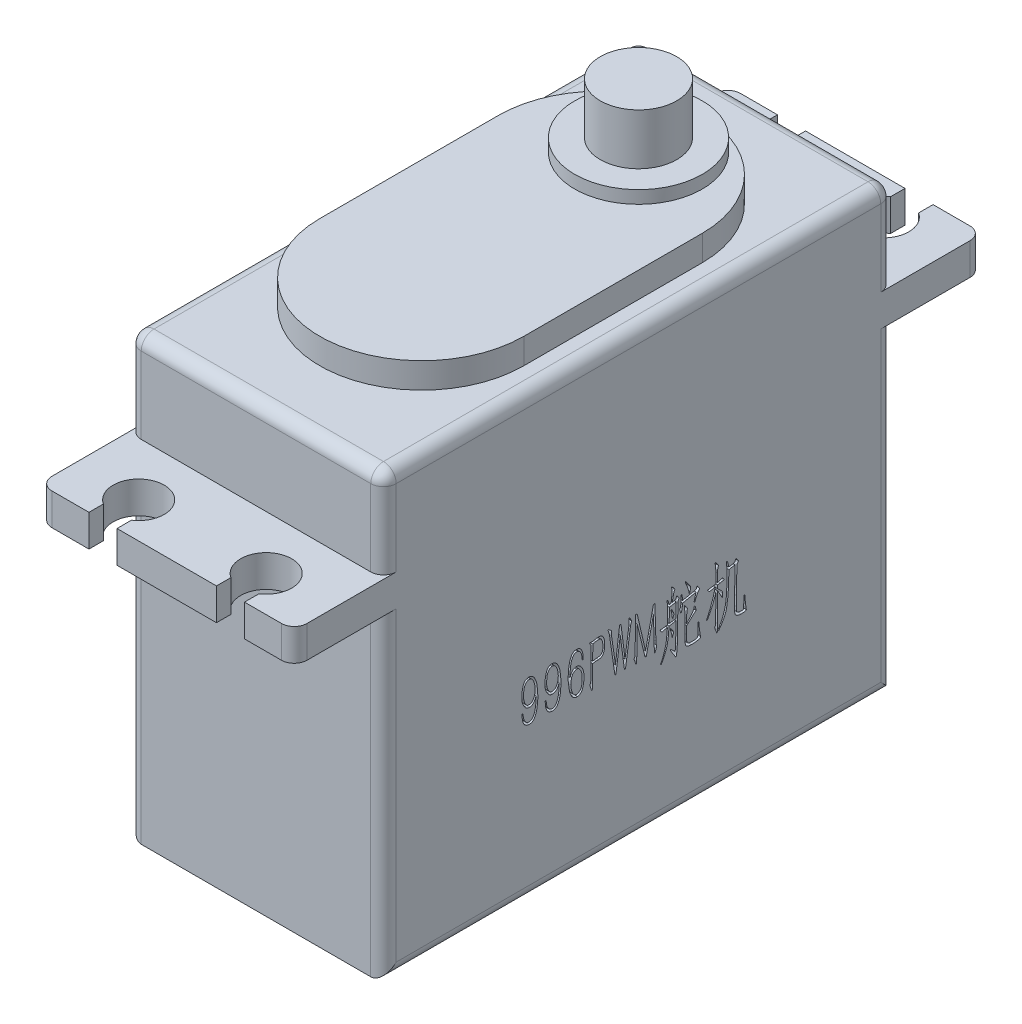
SolidWorks part; units mm, degrees
material "6061 合金"
ref_plane "前视基准面" through (0, 0, 0) normal (0, 0, 1) x (1, 0, 0)
ref_plane "上视基准面" through (0, 0, 0) normal (0, 1, 0) x (1, 0, 0)
ref_plane "右视基准面" through (0, 0, 0) normal (1, 0, 0) x (0, 0, -1)
sketch "草图1" plane through (0, 0, 0) normal (0, 1, 0) x (1, 0, 0)
  line L1 (-10, -20) -> (10, -20)
  line L2 (-10, -20) -> (-10, 20)
  line L3 (-10, 20) -> (10, 20)
  line L4 (10, -20) -> (10, 20)
  line L5 (-10, -20) -> (10, 20) construction
  line L6 (-10, 20) -> (10, -20) construction
  point P0 (0, 0)
  dimension "D1" = 20
  dimension "D2" = 40
extrude "凸台-拉伸1" add sketch "草图1" along normal blind 34.5
sketch "草图2" plane through (0, 34.5, 0) normal (0, 1, 0) x (1, 0, 0)
  line L0 (0, -7) -> (0, 7) construction
  line L1 (-8, -7) -> (-8, 7)
  line L2 (8, -7) -> (8, 7)
  arc A0 (-8, -7) -> (8, -7) centre (0, -7) ccw
  arc A1 (8, 7) -> (-8, 7) centre (0, 7) ccw
  point P2 (0, 0)
  point P8 (0, 15)
  point P9 (0, -15)
  dimension "D1" = 8
  dimension "D2" = 30
extrude "凸台-拉伸2" add sketch "草图2" along normal blind 2
ref_plane "基准面1" through (0, 25, 0) normal (0, -1, 0) x (-1, 0, 0)
sketch "草图3" plane through (0, 25, 0) normal (0, -1, 0) x (-1, 0, 0)
  line L0 (-6.1, 27) -> (-6.1, 25.8703)
  line L1 (-9, -27) -> (-6.1, -27)
  line L2 (-10, -26) -> (-10, 26)
  line L3 (-9, 27) -> (-6.1, 27)
  line L4 (10, -26) -> (10, 26)
  line L5 (-10, -27) -> (10, 27) construction
  line L6 (-10, 27) -> (10, -27) construction
  line L7 (-5, -24.2) -> (5, -24.2) construction
  line L8 (-5, -24.2) -> (-5, 24.2) construction
  line L9 (-5, 24.2) -> (5, 24.2) construction
  line L10 (5, -24.2) -> (5, 24.2) construction
  line L11 (-5, -24.2) -> (5, 24.2) construction
  line L12 (-5, 24.2) -> (5, -24.2) construction
  line L13 (-3.9, 27) -> (-3.9, 25.8703)
  line L14 (0, 27) -> (0, -27) construction
  line L15 (3.9, 27) -> (3.9, 25.8703)
  line L16 (6.1, 27) -> (6.1, 25.8703)
  line L17 (-10, 0) -> (10, 0) construction
  line L18 (6.1, -27) -> (6.1, -25.8703)
  line L19 (3.9, -27) -> (3.9, -25.8703)
  line L20 (-3.9, -27) -> (-3.9, -25.8703)
  line L21 (-6.1, -27) -> (-6.1, -25.8703)
  line L22 (6.1, 27) -> (9, 27)
  line L23 (-3.9, 27) -> (3.9, 27)
  line L24 (-3.9, -27) -> (3.9, -27)
  line L25 (6.1, -27) -> (9, -27)
  arc A0 (-6.1, 25.8703) -> (-3.9, 25.8703) centre (-5, 24.2) ccw
  arc A1 (3.9, 25.8703) -> (6.1, 25.8703) centre (5, 24.2) ccw
  arc A2 (-3.9, -25.8703) -> (-6.1, -25.8703) centre (-5, -24.2) ccw
  arc A3 (6.1, -25.8703) -> (3.9, -25.8703) centre (5, -24.2) ccw
  arc A4 (-9, -27) -> (-10, -26) centre (-9, -26) cw
  arc A5 (9, -27) -> (10, -26) centre (9, -26) ccw
  arc A6 (9, 27) -> (10, 26) centre (9, 26) cw
  arc A7 (-10, 26) -> (-9, 27) centre (-9, 26) cw
  point P0 (0, 0)
  point P6 (0, 0)
  dimension "D4" = 4
  dimension "D6" = 1
  dimension "D1" = 20
  dimension "D2" = 54
  dimension "D3" = 48.4
  dimension "D5" = 2.2
  dimension "D7" = 10
extrude "凸台-拉伸3" add sketch "草图3" against normal blind 2.5
sketch "草图4" plane through (0, 36.5, 0) normal (0, 1, 0) x (1, 0, 0)
  line L0 (-3.9, 27) -> (3.9, 27) construction
  circle A0 centre (0, 10) radius 5
  dimension "D2" = 10
  dimension "D1" = 17
extrude "凸台-拉伸4" add sketch "草图4" along normal blind 1
sketch "草图5" plane through (0, 37.5, 0) normal (0, 1, 0) x (1, 0, 0)
  circle A0 centre (0, 10) radius 3
  dimension "D1" = 6
extrude "凸台-拉伸5" add sketch "草图5" along normal blind 4
fillet "圆角1" radius 1 14 edges at (10, 31, -20) (10, 31, 20) (10, 12.5, 20) (10, 12.5, -20) (10, 0, 0) (-10, 0, 0) (-10, 12.5, 20) (-10, 31, 20) (0, 34.5, 20) (10, 34.5, 0) (0, 34.5, -20) (-10, 34.5, 0) (-10, 31, -20) (-10, 12.5, -20)
sketch "草图6" plane through (10, 0, 0) normal (1, 0, 0) x (0, 0, -1)
  text T0 "996PWM舵机"
extrude "切除-拉伸1" cut sketch "草图6" against normal blind 4
